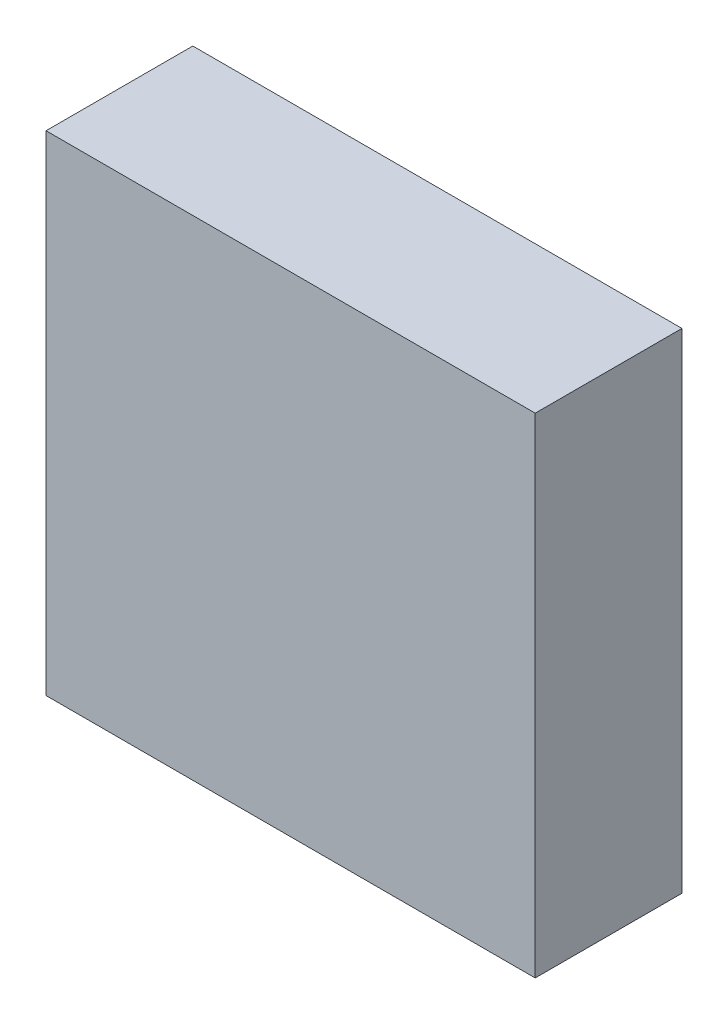
SolidWorks part; units mm, degrees
ref_plane "前基準面" through (0, 0, 0) normal (0, 0, 1) x (1, 0, 0)
ref_plane "上基準面" through (0, 0, 0) normal (0, 1, 0) x (1, 0, 0)
ref_plane "右基準面" through (0, 0, 0) normal (1, 0, 0) x (0, 0, -1)
sketch "草圖1" plane through (0, 0, 0) normal (0, 0, 1) x (1, 0, 0)
  line L1 (-7.7612, 11.0573) -> (12.2388, 11.0573)
  line L2 (-7.7612, 11.0573) -> (-7.7612, -8.9427)
  line L3 (-7.7612, -8.9427) -> (12.2388, -8.9427)
  line L4 (12.2388, 11.0573) -> (12.2388, -8.9427)
  dimension "D1" = 20
  dimension "D2" = 20
extrude "填料-伸長1" add sketch "草圖1" along normal blind 6
sketch "草圖2" plane through (0, 0, 6) normal (0, 0, 1) x (1, 0, 0)
  line L0 (-7.7612, -8.9427) -> (12.2388, -8.9427) construction
  line L1 (5.2388, -4.3905) -> (12.2388, -4.3905)
  line L2 (5.2388, -4.3905) -> (5.2388, -8.9427)
  line L3 (5.2388, -8.9427) -> (12.2388, -8.9427)
  line L4 (12.2388, -4.3905) -> (12.2388, -8.9427)
  line L6 (12.2388, -8.9427) -> (12.2388, 11.0573) construction
  dimension "D2" = 7
extrude "除料-伸長1" [suppressed] cut sketch "草圖2" against normal through all
